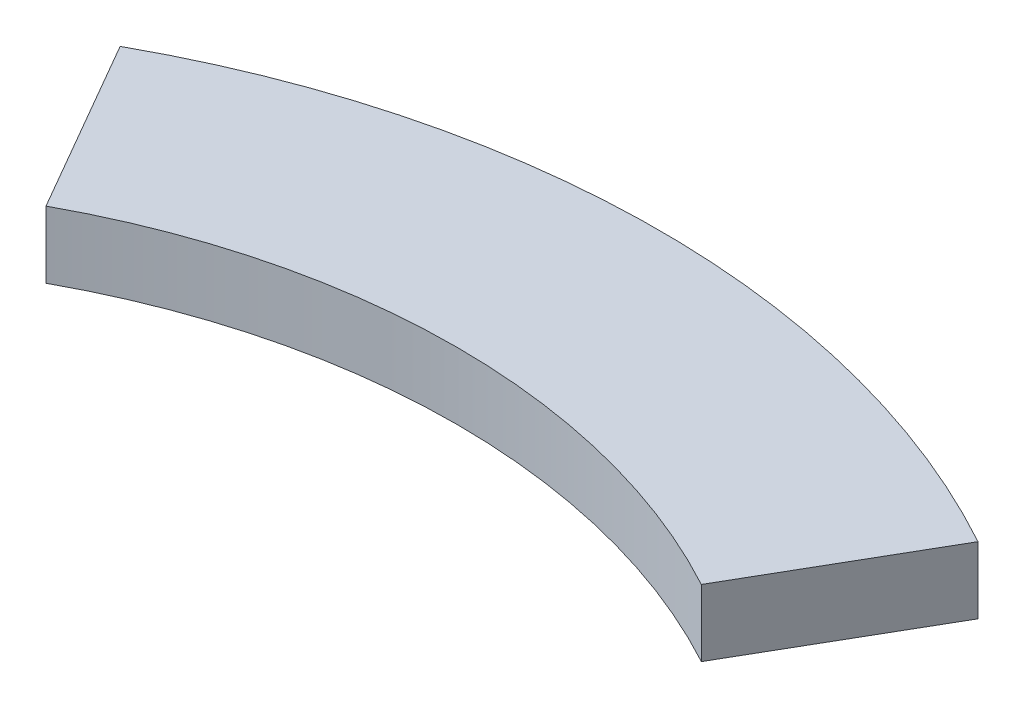
SolidWorks part; units mm, degrees
ref_plane "Front Plane" through (0, 0, 0) normal (0, 0, 1) x (1, 0, 0)
ref_plane "Top Plane" through (0, 0, 0) normal (0, 1, 0) x (1, 0, 0)
ref_plane "Right Plane" through (0, 0, 0) normal (1, 0, 0) x (0, 0, -1)
sketch "Sketch1" plane through (0, 0, 0) normal (0, 1, 0) x (1, 0, 0)
  line L0 (-14, 24.2487) -> (-19, 32.909) construction
  line L1 (14, 24.2487) -> (19, 32.909) construction
  line L2 (0, 0) -> (4, 0) construction
  line L3 (-17.9717, 32.6279) -> (-13.7293, 25.2798)
  line L4 (17.9717, 32.6279) -> (13.7293, 25.2798)
  line L5 (-16.5, 28.5788) -> (-15.8505, 28.9538) construction
  line L6 (15.8505, 28.9538) -> (16.5, 28.5788) construction
  circle A0 centre (0, 0) radius 28 construction
  circle A1 centre (0, 0) radius 38 construction
  arc A2 (-17.9717, 32.6279) -> (17.9717, 32.6279) centre (0, 0) cw
  arc A3 (-13.7293, 25.2798) -> (13.7293, 25.2798) centre (0, 0) cw
  point P19 (16.5, 28.5788)
  dimension "D1" = 28
  dimension "D2" = 38
  dimension "D4" = 0.75
  dimension "D6" = 60
  dimension "D3" = 60
  dimension "D5" = 0.75
extrude "Boss-Extrude1" add sketch "Sketch1" along normal blind 2.8
sketch "Sketch2" plane through (0, 0, 0) normal (0, -1, 0) x (1, 0, 0)
  line L0 (0, -37.25) -> (0, -28.7673) construction
  arc A0 (-17.9717, -32.6279) -> (17.9717, -32.6279) centre (0, 0) ccw construction
  arc A1 (-13.7293, -25.2798) -> (13.7293, -25.2798) centre (0, 0) ccw construction
  circle A2 centre (0, -33.0087) radius 1.625
  dimension "D1" = 3.25
extrude "Cut-Extrude1" cut sketch "Sketch2" against normal blind 2
